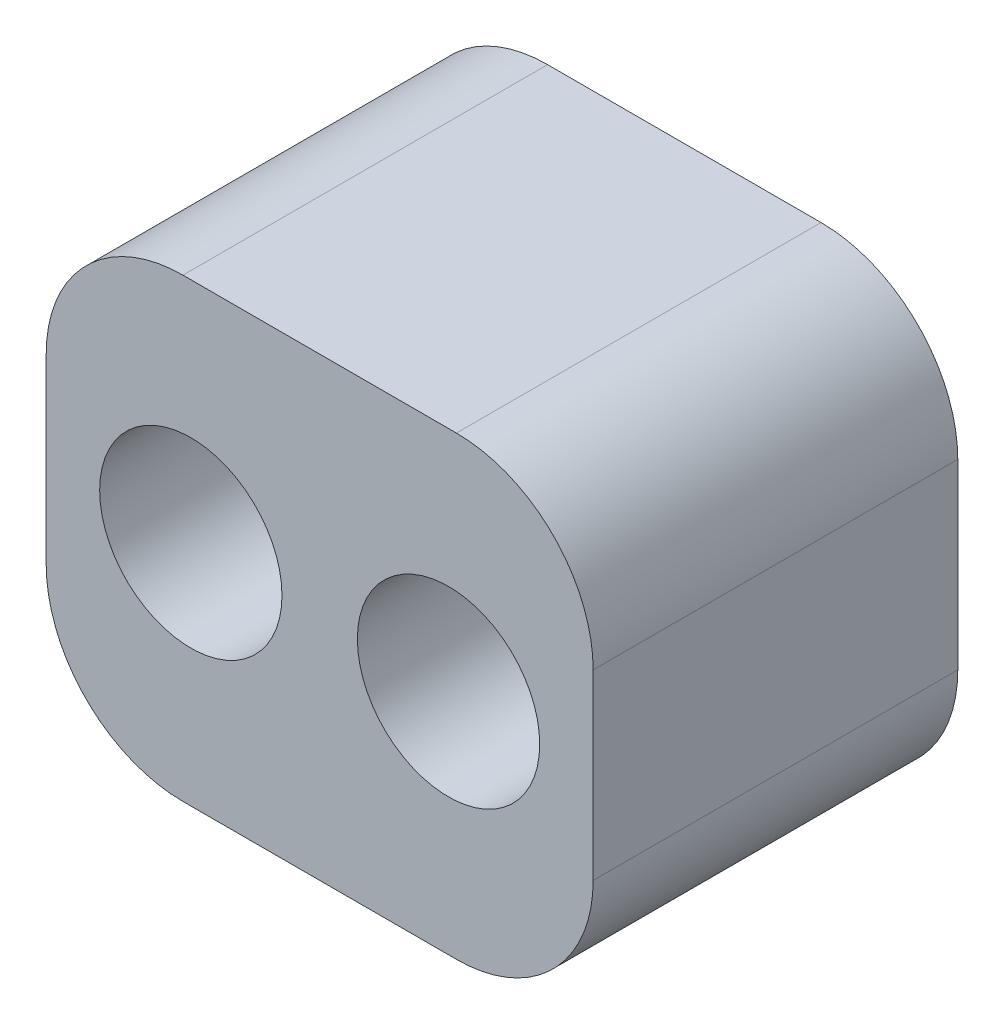
SolidWorks part; units mm, degrees
ref_plane "Front Plane" through (0, 0, 0) normal (0, 0, 1) x (1, 0, 0)
ref_plane "Top Plane" through (0, 0, 0) normal (0, 1, 0) x (1, 0, 0)
ref_plane "Right Plane" through (0, 0, 0) normal (1, 0, 0) x (0, 0, -1)
sketch "Sketch1" plane through (0, 0, 0) normal (0, 0, 1) x (1, 0, 0)
  line L0 (0, 3.4132) -> (0, -3.7606) construction
  line L1 (-3, 2.5) -> (3, 2.5)
  line L2 (-3, 2.5) -> (-3, -2.5)
  line L3 (-3, -2.5) -> (3, -2.5)
  line L4 (3, 2.5) -> (3, -2.5)
  line L5 (-3, 2.5) -> (3, -2.5) construction
  line L6 (-3, -2.5) -> (3, 2.5) construction
  circle A0 centre (1.4136, 0) radius 1
  circle A1 centre (-1.4136, 0) radius 1
  point P0 (0, 0)
  dimension "D1" = 6
  dimension "D2" = 5
  dimension "D3" = 2
extrude "Boss-Extrude1" add sketch "Sketch1" along normal blind 4
fillet "Fillet1" radius 1.5 4 edges at (3, -2.5, 2) (-3, -2.5, 2) (3, 2.5, 2) (-3, 2.5, 2)
